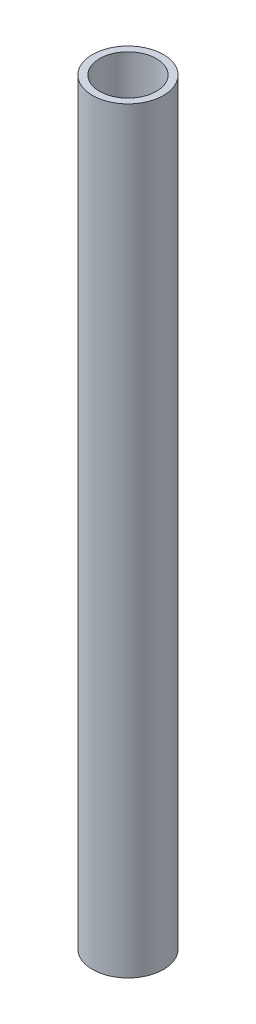
SolidWorks part; units mm, degrees
ref_plane "Front Plane" through (0, 0, 0) normal (0, 0, 1) x (1, 0, 0)
ref_plane "Top Plane" through (0, 0, 0) normal (0, 1, 0) x (1, 0, 0)
ref_plane "Right Plane" through (0, 0, 0) normal (1, 0, 0) x (0, 0, -1)
sketch "Sketch1" plane through (0, 0, 0) normal (0, 1, 0) x (1, 0, 0)
  circle A0 centre (0, 0) radius 15
  circle A1 centre (0, 0) radius 12
  dimension "D1" = 30
  dimension "D2" = 24
extrude "Boss-Extrude1" add sketch "Sketch1" along normal blind 320
